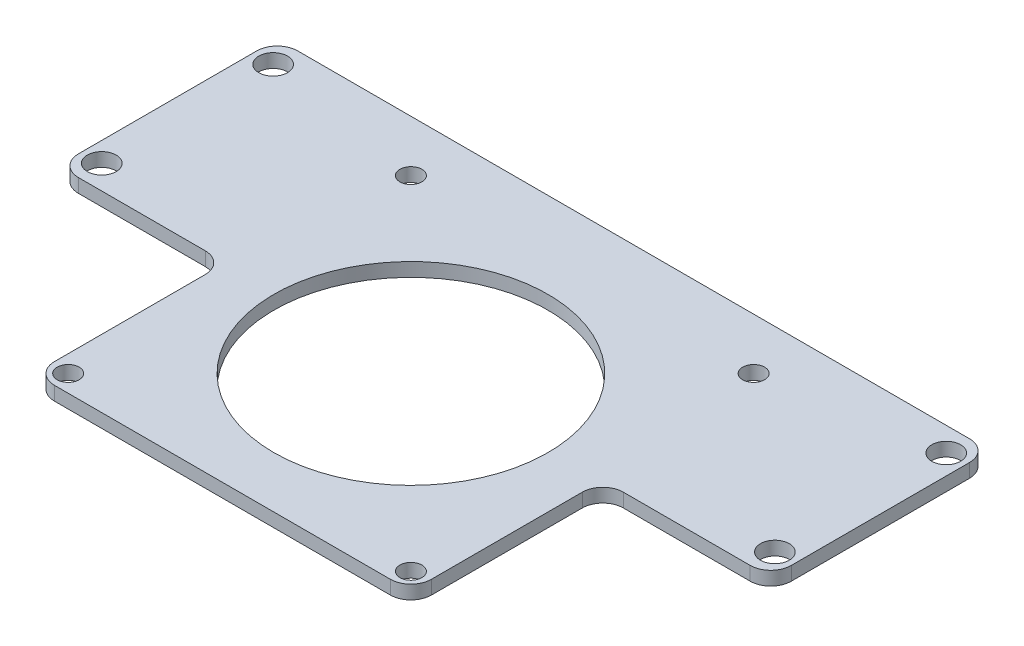
SolidWorks part; units mm, degrees
material "Thornel Mat VMA"
ref_plane "前视基准面" through (0, 0, 0) normal (0, 0, 1) x (1, 0, 0)
ref_plane "上视基准面" through (0, 0, 0) normal (0, 1, 0) x (1, 0, 0)
ref_plane "右视基准面" through (0, 0, 0) normal (1, 0, 0) x (0, 0, -1)
sketch "草图1" plane through (0, 0, 0) normal (0, 1, 0) x (1, 0, 0)
  line L0 (49.1, 12.5) -> (-49.1, 12.5) construction
  line L1 (-52, 16) -> (52, 16)
  line L2 (-52, 16) -> (-52, -16)
  line L3 (-52, -16) -> (52, -16)
  line L4 (52, 16) -> (52, -16)
  line L5 (-52, 16) -> (52, -16) construction
  line L6 (-52, -16) -> (52, 16) construction
  line L7 (0, 0) -> (0, 48.5931) construction
  line L8 (-49.1, 12.5) -> (-49.1, -12.5) construction
  line L9 (0, 0) -> (-63.5413, 0) construction
  line L10 (-25, 8.5) -> (25, 8.5) construction
  line L11 (-25, 8.5) -> (-25, -41.5) construction
  line L12 (-25, -41.5) -> (-25, -16) construction
  line L13 (-25, -41.5) -> (0, -41.5) construction
  line L14 (25, -41.5) -> (0, -41.5) construction
  line L15 (25, -41.5) -> (25, -16)
  line L16 (0, 0) -> (0, -62.887) construction
  line L17 (-27.5, -44) -> (27.5, -44)
  line L18 (-27.5, -44) -> (-27.5, -16)
  line L19 (27.5, -44) -> (27.5, -16)
  line L20 (-25, 8.5) -> (25, -41.5) construction
  circle A0 centre (-49.1, 12.5) radius 2.1
  circle A1 centre (-49.1, -12.5) radius 2.1
  circle A2 centre (-25, -41.5) radius 1.6
  circle A3 centre (-25, 8.5) radius 1.6
  circle A4 centre (25, -41.5) radius 1.6
  circle A5 centre (49.1, -12.5) radius 2.1
  circle A6 centre (25, 8.5) radius 1.6
  circle A7 centre (49.1, 12.5) radius 2.1
  circle A8 centre (0, -16.5) radius 20
  point P0 (0, 0)
  point P9 (0, 12.5)
  point P33 (0, -41.5)
  point P34 (0, -44)
  dimension "D4" = 4.2
  dimension "D6" = 4.2
  dimension "D10" = 3.2
  dimension "D11" = 3.2
  dimension "D15" = 40
  dimension "D1" = 104
  dimension "D2" = 32
  dimension "D3" = 98.2
  dimension "D5" = 25
  dimension "D7" = 50
  dimension "D8" = 7.5
  dimension "D9" = 50
  dimension "D12" = 55
  dimension "D13" = 2.5
  dimension "D14" = 2.5
extrude "凸台-拉伸1" add sketch "草图1" along normal blind 2 contours L4 L1 L2 L3 A6 A0 A1 A3 A5 A7 | L14 A4 L15 L3 L12 A2 L13
fillet "圆角1" radius 3 8 edges at (52, 1, -16) (52, 1, 16) (27.5, 1, 16) (27.5, 1, 44) (-27.5, 1, 44) (-27.5, 1, 16) (-52, 1, 16) (-52, 1, -16)
